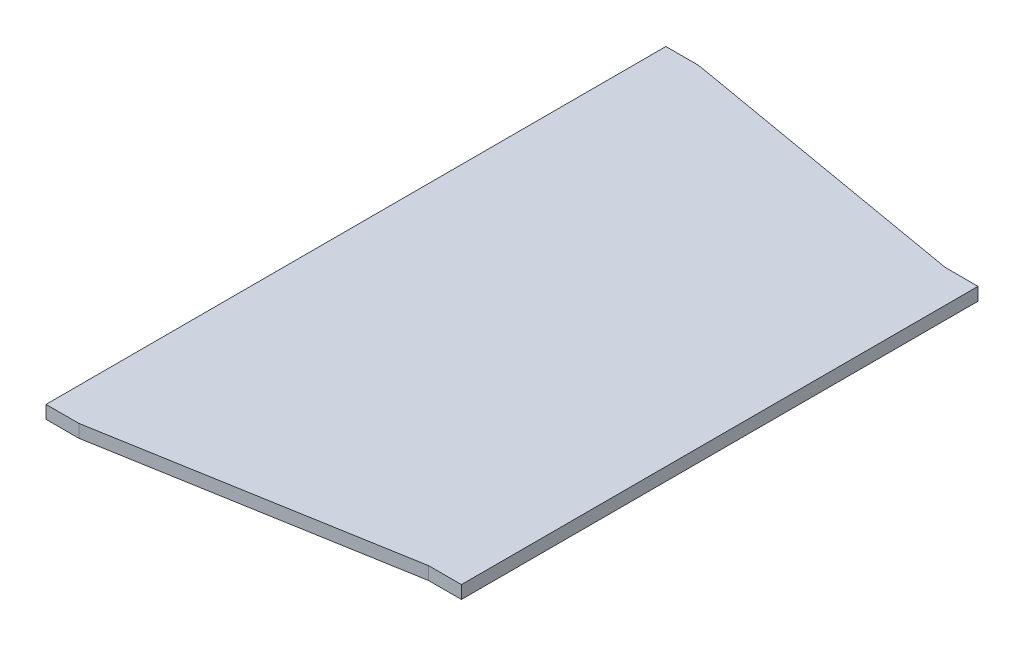
SolidWorks part; units mm, degrees
ref_plane "Front Plane" through (0, 0, 0) normal (0, 0, 1) x (1, 0, 0)
ref_plane "Top Plane" through (0, 0, 0) normal (0, 1, 0) x (1, 0, 0)
ref_plane "Right Plane" through (0, 0, 0) normal (1, 0, 0) x (0, 0, -1)
sketch "Sketch1" plane through (0, 0, 0) normal (0, 1, 0) x (1, 0, 0)
  line L1 (230.87, 200) -> (256.27, 200)
  line L3 (230.87, -200) -> (256.27, -200)
  line L4 (256.27, 200) -> (256.27, -200)
  line L5 (0, 240) -> (-25.4, 240)
  line L7 (0, -240) -> (-25.4, -240)
  line L8 (-25.4, 240) -> (-25.4, -240)
  spline S0 degree 1 poles (0, 240) (230.87, 200) knots 0 0 1 1 construction
  spline S1 degree 1 poles (0, 240) (230.87, 200) knots 0 0 1 1
  spline S2 degree 1 poles (0, -240) (230.87, -200) knots 0 0 1 1 construction
  spline S3 degree 1 poles (0, -240) (230.87, -200) knots 0 0 1 1
  dimension "D1" = 25.4
  dimension "D2" = 25.4
extrude "Boss-Extrude1" add sketch "Sketch1" along normal blind 10
